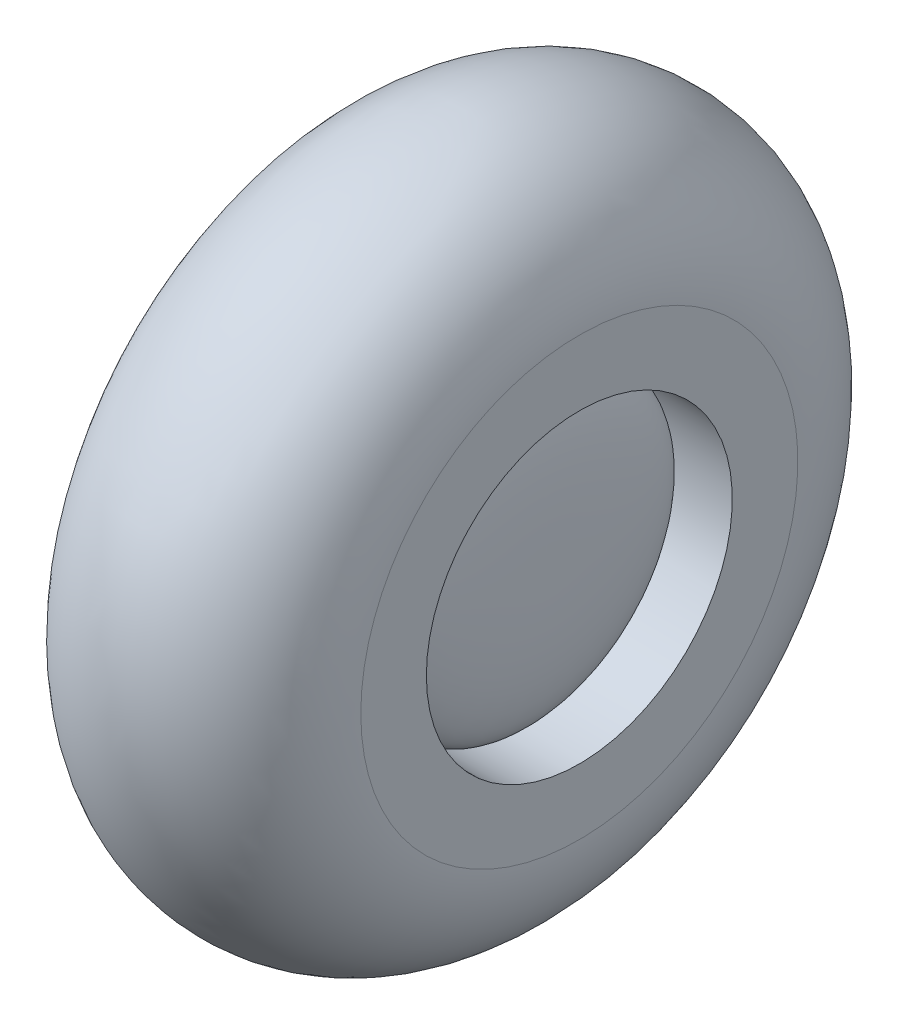
SolidWorks part; units mm, degrees
material "Choose your Material"
ref_plane "Front Plane" through (0, 0, 0) normal (0, 0, 1) x (1, 0, 0)
ref_plane "Top Plane" through (0, 0, 0) normal (0, 1, 0) x (1, 0, 0)
ref_plane "Right Plane" through (0, 0, 0) normal (1, 0, 0) x (0, 0, -1)
sketch "Sketch3" plane through (0, 0, 0) normal (0, 0, 1) x (1, 0, 0)
  line L0 (0, 0) -> (54643.4738, 0) construction
  line L1 (-66.675, 0) -> (66.675, 0)
  line L3 (-88.9, 104.4575) -> (-88.9, 149.225)
  line L4 (-88.9, 104.4575) -> (-44.45, 104.4575)
  line L5 (-66.675, 104.4575) -> (-66.675, 0) construction
  line L6 (-66.675, -68.6429) -> (-66.675, 68.7741) construction
  line L7 (-73.037, 104.4575) -> (-37.1122, 104.4575) construction
  line L8 (0, 0) -> (0, 149.225) construction
  line L9 (88.9, 104.4575) -> (88.9, 149.225)
  line L10 (66.675, 104.4575) -> (66.675, 0) construction
  line L11 (88.9, 104.4575) -> (44.45, 104.4575)
  arc A0 (-88.9, 149.225) -> (88.9, 149.225) centre (0, 149.225) cw
  spline S0 degree 3 poles (-44.45, 104.4575) (-66.903, 104.4575) (-66.675, 43.6827) (-66.675, 0) knots 0 0 0 0 1 1 1 1
  spline S1 degree 3 poles (44.45, 104.4575) (66.903, 104.4575) (66.675, 43.6827) (66.675, 0) knots 0 0 0 0 1 1 1 1
  point P6 (0, 0)
  dimension "D2" = 88.9
  dimension "D1" = 149.225
  dimension "D3" = 104.4575
  dimension "D4" = 44.45
revolve "Revolve1" add sketch "Sketch3" angle 360 about L0
equation "\"wheelwidth\" = 7"
equation "\"D2@Sketch3\"=\"wheelwidth\"/2"
equation "\"diameter\"= 18.75"
equation "\"D1@Sketch3\"=\"diameter\"/2-\"wheelwidth\"/2"
equation "\"D3@Sketch3\"=(\"diameter\"/2-\"wheelwidth\"/2)*0.7"
equation "\"D4@Sketch3\"=\"wheelwidth\"/4"
